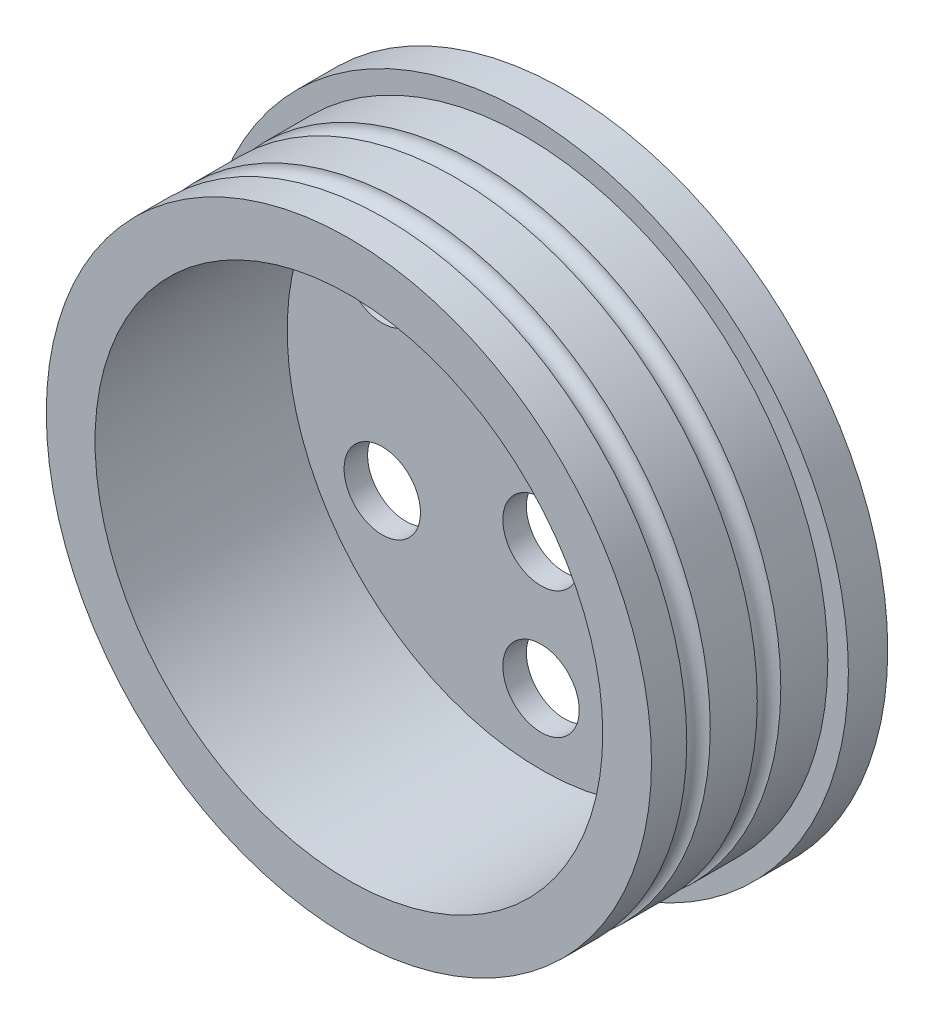
SolidWorks part; units mm, degrees
material "PVC 0.007 Plastificado"
ref_plane "Alzado" through (0, 0, 0) normal (0, 0, 1) x (1, 0, 0)
ref_plane "Planta" through (0, 0, 0) normal (0, 1, 0) x (1, 0, 0)
ref_plane "Vista lateral" through (0, 0, 0) normal (1, 0, 0) x (0, 0, -1)
sketch "Croquis1" plane through (0, 0, 0) normal (0, 0, 1) x (1, 0, 0)
  circle A0 centre (0, 0) radius 55
  dimension "D1" = 110
extrude "Saliente-Extruir1" add sketch "Croquis1" along normal blind 6.7
sketch "Croquis2" plane through (0, 0, 6.7) normal (0, 0, 1) x (1, 0, 0)
  circle A0 centre (0, 0) radius 51.5
  dimension "D1" = 103
extrude "Saliente-Extruir2" add sketch "Croquis2" along normal blind 30
sketch "Croquis3" plane through (0, 0, 0) normal (0, 1, 0) x (1, 0, 0)
  line L0 (-51.5, -6.7) -> (-51.5, -36.7) construction
  line L1 (-51.5, -6.7) -> (51.5, -6.7) construction
  line L2 (-51.5, -36.7) -> (51.5, -36.7) construction
  circle A0 centre (-51.5, -16.7) radius 2
  circle A2 centre (-51.5, -28.7) radius 2
  dimension "D1" = 4
  dimension "D2" = 10
  dimension "D3" = 8
sketch "Rev axis" plane through (0, 0, 0) normal (0, 1, 0) x (1, 0, 0)
  line L0 (0, -36.878) -> (0, 0) construction
revolve "Cortar-Revolución1" cut sketch "Croquis3" angle 360 about L0
sketch "Croquis4" plane through (0, 0, 36.7) normal (0, 0, 1) x (1, 0, 0)
  circle A0 centre (0, 0) radius 43.2
  circle A1 centre (0, 0) radius 51.5 construction
  dimension "D1" = 8.3
extrude "Cortar-Extruir1" cut sketch "Croquis4" against normal offset from surface (32.7 mm away) 4 up to face at (55, 0, 0)
sketch "Croquis5" plane through (0, 0, 0) normal (0, 0, -1) x (-1, 0, 0)
  circle A0 centre (0, 0) radius 31.2
  circle A1 centre (0, 0) radius 55 construction
  circle A2 centre (31.2, 0) radius 12
  circle A3 centre (0, 0) radius 43.2 construction
  point P0 (0, 31.2)
  point P12 (22.0617, 22.0617)
  point P13 (31.2, 0)
  point P14 (22.0617, -22.0617)
  point P17 (0, -31.2)
  point P18 (-22.0617, -22.0617)
  point P19 (0, 0)
  point P21 (-31.2, 0)
  point P22 (-22.0617, 22.0617)
  dimension "D1" = 24
  dimension "D2" = 8
hole_wizard "Taladro de margen para M121" positions "Croquis10" profile "Croquis11" hole size "M12" standard "AS" end condition through all
sketch "Croquis10" plane through (0, 0, 0) normal (0, 0, -1) x (-1, 0, 0)
  point P0 (0, 31.2)
sketch "Croquis11" plane through (0, 31.2, 0) normal (1, 0, 0) x (0, 1, 0)
  line L0 (0, 0) -> (0, 36.7)
  line L1 (0, 36.7) -> (6.5, 36.7)
  line L2 (6.5, 36.7) -> (6.5, 0)
  line L5 (6.5, 0) -> (0, 0)
  line L11 (0, -6.35) -> (0, 107.95) construction
  dimension "Diámetro de taladro hasta el siguiente" = 13
  dimension "Profundidad de taladro hasta el siguiente" = 36.7
pattern_circular "MatrizC1" count 6 over 360 about axis through (0, 0, 0) along (0, 0, 1) of "Taladro de margen para M121"
sketch "Croquis12" [suppressed] plane through (0, 0, 0) normal (0, 0, -1) x (-1, 0, 0)
  circle A0 centre (0, 0) radius 46.5
  circle A2 centre (0, 0) radius 51.5 construction
  dimension "D1" = 5
extrude "Cortar-Extruir2" [suppressed] cut sketch "Croquis12" against normal through all both and the other way through all
sketch "Croquis13" plane through (0, 0, 0) normal (0, 0, -1) x (-1, 0, 0)
  point P0 (0, -9.6)
  point P8 (-27.02, -15.6)
  dimension "D1" = 9.6
hole_wizard "Taladro de margen para M122" positions "Croquis14" profile "Croquis15" hole size "M12" standard "BSI" end condition through all
sketch "Croquis14" plane through (0, 0, 0) normal (0, 0, -1) x (-1, 0, 0)
  point P0 (0, -9.6)
sketch "Croquis15" plane through (0, -9.6, 0) normal (1, 0, 0) x (0, 1, 0)
  line L0 (0, 0) -> (0, 36.7)
  line L1 (0, 36.7) -> (6.5, 36.7)
  line L2 (6.5, 36.7) -> (6.5, 0)
  line L5 (6.5, 0) -> (0, 0)
  line L11 (0, -6.35) -> (0, 107.95) construction
  dimension "Diámetro de taladro hasta el siguiente" = 13
  dimension "Profundidad de taladro hasta el siguiente" = 36.7
mirror "Simetría1" about plane through (0, 0, 0) normal (0, 1, 0) of "Taladro de margen para M122"
equation "\"D1@Croquis13\"=(38.4/2)/2"
